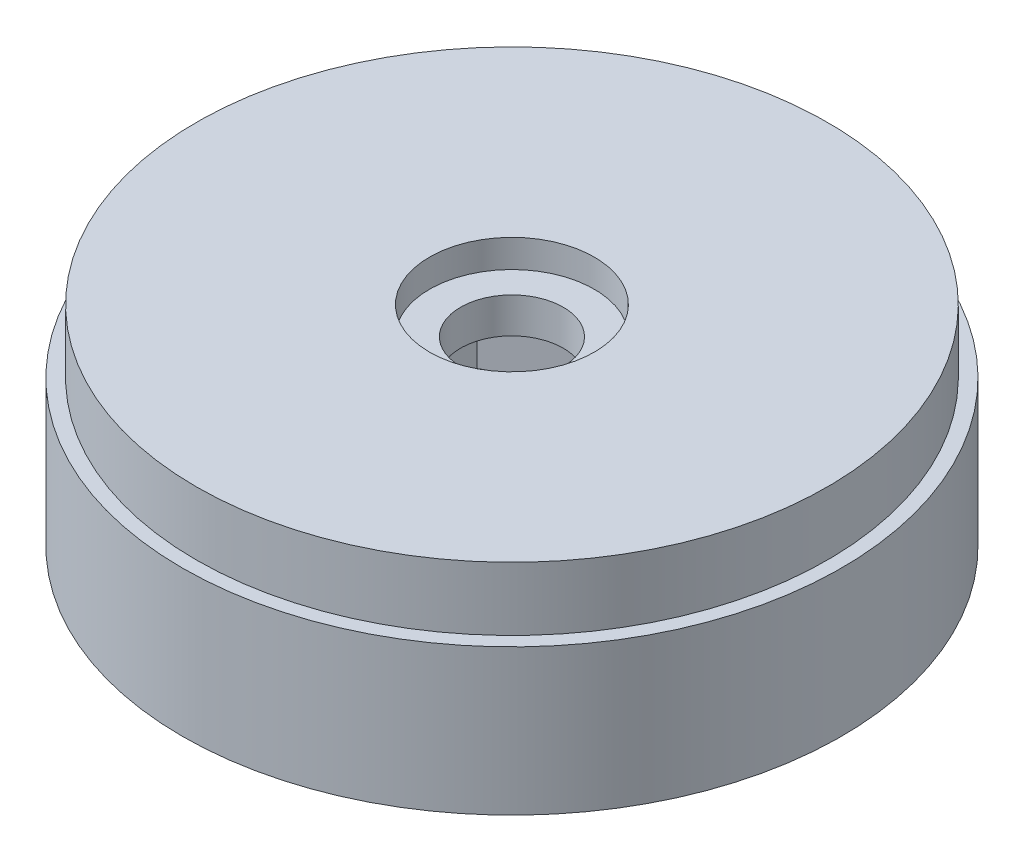
SolidWorks part; units mm, degrees
ref_plane "Front Plane" through (0, 0, 0) normal (0, 0, 1) x (1, 0, 0)
ref_plane "Top Plane" through (0, 0, 0) normal (0, 1, 0) x (1, 0, 0)
ref_plane "Right Plane" through (0, 0, 0) normal (1, 0, 0) x (0, 0, -1)
sketch "Sketch1" plane through (0, 0, 0) normal (0, 1, 0) x (1, 0, 0)
  line L1 (0, 7.5056) -> (-6.5, 3.7528)
  line L2 (-6.5, 3.7528) -> (-6.5, -3.7528)
  line L3 (-6.5, -3.7528) -> (0, -7.5056)
  line L4 (0, -7.5056) -> (6.5, -3.7528)
  line L5 (6.5, -3.7528) -> (6.5, 3.7528)
  line L6 (6.5, 3.7528) -> (0, 7.5056)
  circle A0 centre (0, 0) radius 26
  circle A1 centre (0, 0) radius 6.5 construction
  dimension "D1" = 52
  dimension "D2" = 13
extrude "Boss-Extrude1" add sketch "Sketch1" along normal blind 11.5
sketch "Sketch2" plane through (0, 11.5, 0) normal (0, 1, 0) x (1, 0, 0)
  circle A0 centre (0, 0) radius 4.05
  circle A1 centre (0, 0) radius 24.9
  circle A2 centre (0, 0) radius 26 construction
  dimension "D1" = 8.1
  dimension "D2" = 1.1
extrude "Boss-Extrude2" add sketch "Sketch2" along normal blind 5
sketch "Sketch3" plane through (0, 0, 0) normal (0, -1, 0) x (1, 0, 0)
  circle A0 centre (0, 0) radius 8
  dimension "D1" = 16
extrude "Cut-Extrude1" cut sketch "Sketch3" against normal blind 7
sketch "Sketch4" plane through (0, 16.5, 0) normal (0, 1, 0) x (1, 0, 0)
  circle A0 centre (0, 0) radius 6.5
  dimension "D1" = 13
extrude "Cut-Extrude2" cut sketch "Sketch4" against normal blind 2.2
